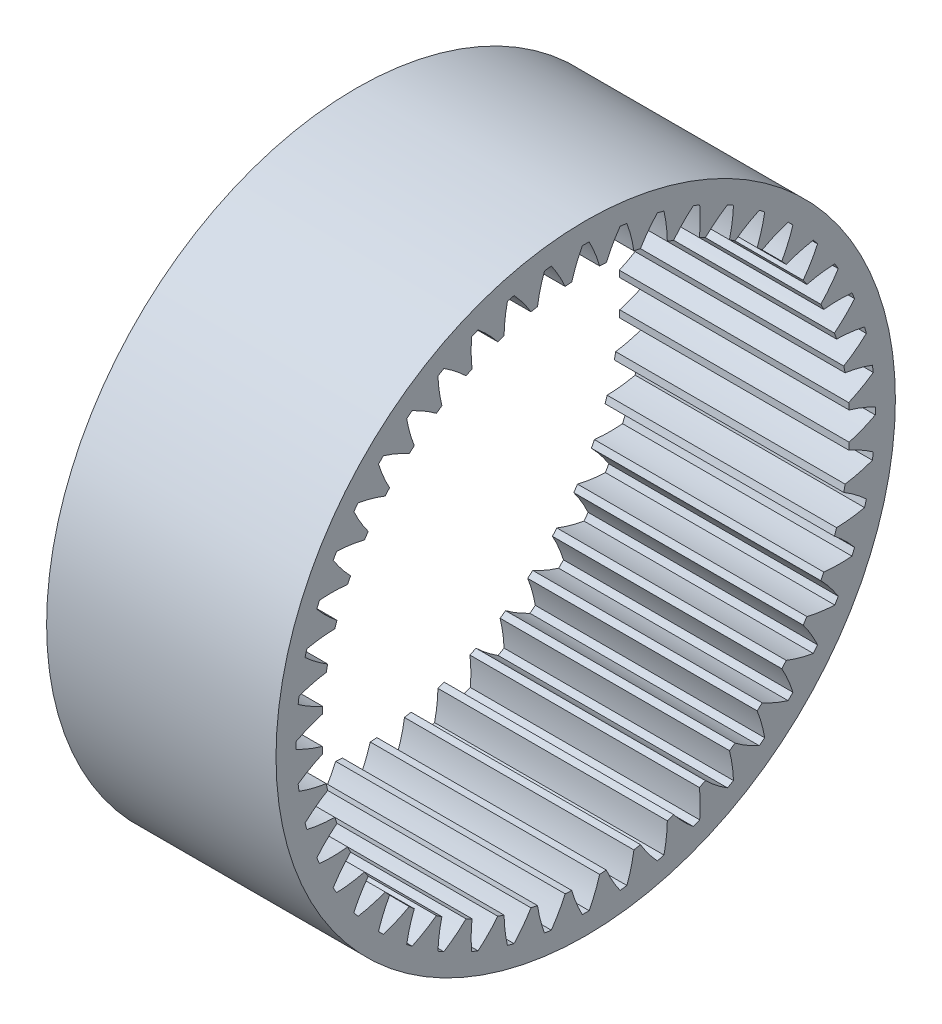
SolidWorks part; units mm, degrees
ref_plane "Plane1" through (0, 0, 0) normal (0, 0, 1) x (1, 0, 0)
ref_plane "Plane2" through (0, 0, 0) normal (0, 1, 0) x (1, 0, 0)
ref_plane "Plane3" through (0, 0, 0) normal (1, 0, 0) x (0, 0, -1)
sketch "HoldingSke" plane through (0, 0, 0) normal (0, 1, 0) x (1, 0, 0)
  line L0 (0, 0) -> (0.2677, -0.2973)
  line L1 (-15, 0) -> (100, 0) construction
  line L2 (0, 0) -> (-2.1039, 2.3779)
  line L3 (0, 0) -> (-11.863, 4.5341)
  line L4 (0, 0) -> (5.7786, 6.4178)
  line L5 (0, 0) -> (-23.7986, -8.8762)
  line L6 (0, 0) -> (-10.5278, -7.1032)
  line L7 (-2.1039, 2.3779) -> (3.3635, 27.1825)
  line L8 (-76.2, 4.8779) -> (-54.61, 4.8779)
  line L9 (-71.009, 38.7566) -> (-53.1078, 45.2721)
  line L10 (-76.2, 71.12) -> (104.1128, 71.12)
  line L11 (0, 0) -> (-50, 0)
  line L12 (-76.2, 101.6) -> (-76.113, 101.6)
  line L13 (24.9733, 27.94) -> (52.9518, 28.4284)
  line L14 (24.9733, 27.94) -> (24.9743, 27.94)
  line L15 (24.9733, 27.94) -> (100.4006, 29.5858)
  circle A0 centre (0, 0) radius 67.5
  circle A1 centre (0, 0) radius 12.7
  circle A2 centre (0, 0) radius 12.7
  dimension "MHD" = 25.4
  dimension "Hub_dia" = 25.4
  dimension "Diameter" = 135
  dimension "Num_teeth" = 48
  dimension "Pitch" = 0.4
  dimension "Overall_len" = 25.4
  dimension "Show_teeth" = 48
  dimension "Thickness" = 12.7
  dimension "OAL" = 25.4001
  dimension "T_dim" = 21.59
  dimension "Ap" = 20
  dimension "H" = 19.05
  dimension "Pitch_radius" = 180.3128
  dimension "Width" = 50
  dimension "Backlash" = 0.087
  dimension "Addendum_fac" = 1
  dimension "Dedendum_fac" = 1.25
  dimension "Clearance_fac" = 0.25
  dimension "Dedendum_add" = 0.001
  dimension "Module" = 2.5
sketch "BasProSke" plane through (0, 0, 0) normal (0, 1, 0) x (1, 0, 0)
  line L0 (-10, 0) -> (60, 0) construction
  line L1 (0, 57.5) -> (0, 67.5)
  line L2 (0, 57.5) -> (50, 57.5)
  line L3 (50, 57.5) -> (50, 67.5)
  line L4 (50, 67.5) -> (0, 67.5)
  dimension "Diameter" = 135
  dimension "Thickness" = 50
  dimension "Inside_diameter" = 115
revolve "Base-Revolve" add sketch "BasProSke" angle 360 about L0
sketch "TooCutSke" plane through (0, 0, 0) normal (1, 0, 0) x (0, 0, -1)
  line L3 (2.1806, 59.9604) -> (2.1806, 53.6633) construction
  line L4 (0, 0) -> (0, 59.563) construction
  line L5 (0, 0) -> (-4.4688, 68.1812) construction
  line L6 (-25.8081, 49.1607) -> (34.443, 53.1098) construction
  circle A0 centre (0, 0) radius 60 construction
  circle A1 centre (0, 0) radius 63.126 construction
  circle A2 centre (0, 0) radius 50.7434 construction
  circle A3 centre (0, 0) radius 57.4746 construction
  arc A4 (3.04, 57.3941) -> (0.7455, 63.1216) centre (-25.8081, 49.1607) ccw
  arc A5 (3.04, 57.3941) -> (-3.04, 57.3941) centre (0, 0) ccw
  arc A6 (0.7455, 63.1216) -> (-0.7455, 63.1216) centre (0, 0) ccw
  arc A7 (-0.7455, 63.1216) -> (-3.04, 57.3941) centre (25.8081, 49.1607) ccw
  dimension "Pitch_dia" = 120
  dimension "Base_dia" = 101.4868
  dimension "Root_dia" = 126.252
  dimension "Overcut_dia" = 114.9492
  dimension "Flank_rad" = 30
  dimension "Half_ang" = 3.75
  dimension "Half_CT" = 2.1806
extrude "ToothCut" cut sketch "TooCutSke" along normal through all
fillet "Breaks" [suppressed] radius 0.25
fillet "RootFillets" [suppressed] radius 0.626
pattern_circular "TeethCuts" count 48 every 7.5 about axis through (-10, 0, 0) along (1, 0, 0) of "RootFillets", "Breaks", "ToothCut"
equation "' \"Module@HoldingSke\" = 6.35"
equation "' \"Num_teeth@HoldingSke\" = 24"
equation "' \"Ap@HoldingSke\" =  14.5"
equation "' \"Ap@HoldingSke\" = 14.5"
equation "' \"Width@HoldingSke\" = 12"
equation "' \"Diameter@HoldingSke\" = 8 * 25.4"
equation "' \"Show_teeth@HoldingSke\" = 100"
equation "' \"Backlash@HoldingSke\" = 0.009 * 25.4"
equation "' \"Addendum_fac@HoldingSke\" = 1.0"
equation "' \"Dedendum_fac@HoldingSke\" = 1.25"
equation "' \"Dedendum_add@HoldingSke\" = 0.00005 * 25.4"
equation "' \"Clearance_fac@HoldingSke\" = 0.25"
equation "\"Pitch@HoldingSke\" = 1 / \"Module@HoldingSke\" "
equation "\"Overcut_dia@TooCutSke\" = (\"Num_teeth@HoldingSke\" - 2 * \"Addendum_fac@HoldingSke\") / \"Pitch@HoldingSke\" - 0.002 * 25.4"
equation "\"Pitch_dia@TooCutSke\" = \"Num_teeth@HoldingSke\" / \"Pitch@HoldingSke\""
equation "\"Base_dia@TooCutSke\" = \"Num_teeth@HoldingSke\" / \"Pitch@HoldingSke\" * cos((\"Ap@HoldingSke\"  * 3.14159265 / 180)) * 0.90"
equation "\"Root_dia@TooCutSke\" = \"Num_teeth@HoldingSke\"  / \"Pitch@HoldingSke\" + 2 *  \"Dedendum_fac@HoldingSke\"/ \"Pitch@HoldingSke\" + \"Dedendum_add@HoldingSke\" * 2"
equation "\"Half_ang@TooCutSke\" = 180 / \"Num_teeth@HoldingSke\""
equation "\"Half_CT@TooCutSke\" = \"Num_teeth@HoldingSke\" / \"Pitch@HoldingSke\" * sin((3.14159265 / 2 / \"Num_teeth@HoldingSke\")) / 2 + 10 * \"Backlash@HoldingSke\" / 4"
equation "\"Flank_rad@TooCutSke\" = \"Num_teeth@HoldingSke\" / \"Pitch@HoldingSke\" / 4"
equation "\"Radius@RootFillets\"= \"Clearance_fac@HoldingSke\" / \"Pitch@HoldingSke\" + \"Dedendum_add@HoldingSke\""
equation "\"Break_rad@Breaks\" = 0.02 / \"Pitch@HoldingSke\" * 5"
equation "\"Num_teeth@TeethCuts\" = int( \"Show_teeth@HoldingSke\" ) + 1"
equation "\"Num_teeth@TeethCuts\" = ((sgn( \"Num_teeth@TeethCuts\" - \"Num_teeth@HoldingSke\" )-1)*( \"Num_teeth@TeethCuts\" - \"Num_teeth@HoldingSke\" ))/-2+ \"Num_teeth@HoldingSke\""
equation "\"Num_teeth@TeethCuts\" = ((sgn( \"Num_teeth@TeethCuts\" - 2.0)+1)*( \"Num_teeth@TeethCuts\" - 2.0))/2 +2.0"
equation "\"Angle@TeethCuts\" = 360.0 / \"Num_teeth@HoldingSke\""
equation "\"Diameter@BasProSke\" = \"Num_teeth@HoldingSke\"  / \"Pitch@HoldingSke\" + 2 *  \"Dedendum_fac@HoldingSke\"/ \"Pitch@HoldingSke\" + \"Dedendum_add@HoldingSke\" * 2 + 0.002 * 25.4"
equation "\"Diameter@BasProSke\" = ((sgn( \"Diameter@BasProSke\"  - \"Diameter@HoldingSke\" )+1)*( \"Diameter@BasProSke\"  - \"Diameter@HoldingSke\" ))/2 + \"Diameter@HoldingSke\""
equation "\"Inside_diameter@BasProSke\" =  (\"Num_teeth@HoldingSke\" - 2 * \"Addendum_fac@HoldingSke\") / \"Pitch@HoldingSke\" "
equation "\"Thickness@BasProSke\"  = \"Width@HoldingSke\""
